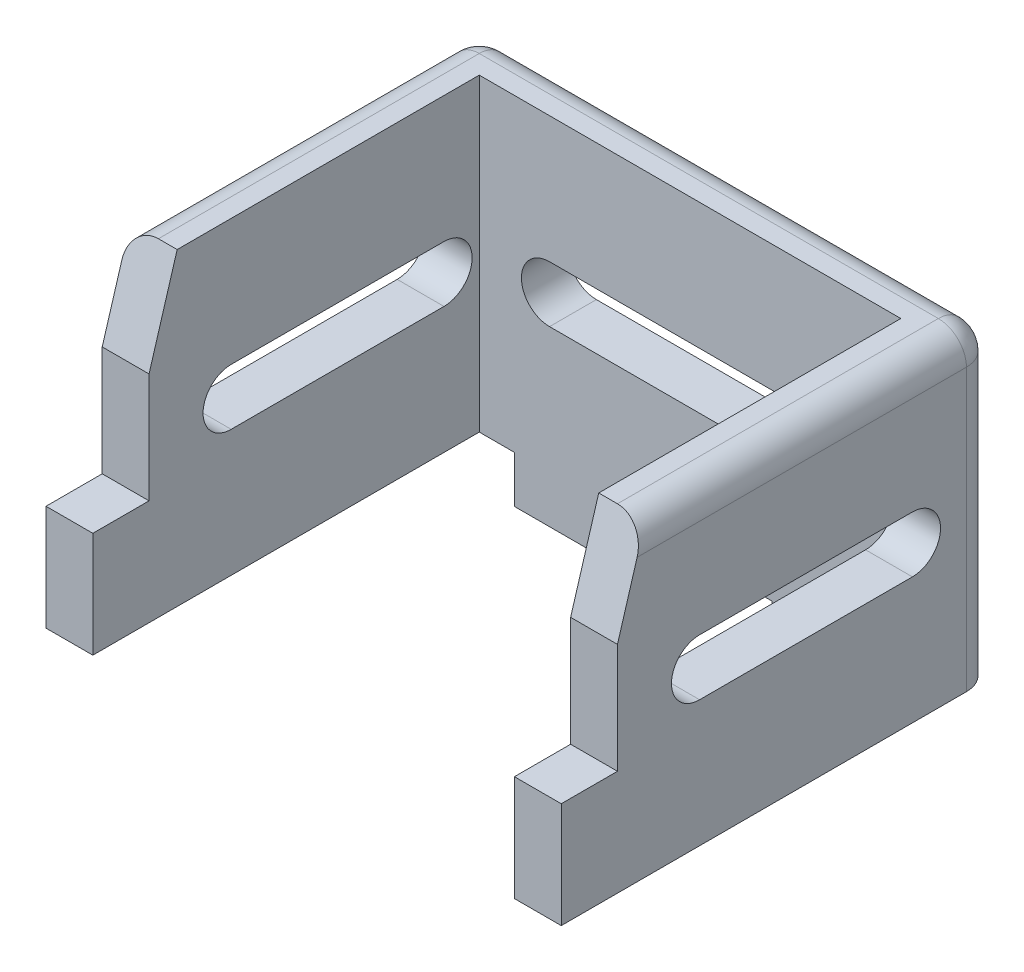
SolidWorks part; units mm, degrees
material "ABS"
ref_plane "Front Plane" through (0, 0, 0) normal (0, 0, 1) x (1, 0, 0)
ref_plane "Top Plane" through (0, 0, 0) normal (0, 1, 0) x (1, 0, 0)
ref_plane "Right Plane" through (0, 0, 0) normal (1, 0, 0) x (0, 0, -1)
sketch "Sketch1" plane through (0, 0, 0) normal (0, 1, 0) x (1, 0, 0)
  line L0 (-18.75, -2.5) -> (-17.25, 2.5)
  line L5 (-18.75, -2.5) -> (-8.75, -2.5) construction
  line L6 (-18.75, -2.5) -> (-18.75, 2.5) construction
  line L7 (-18.75, 2.5) -> (-8.75, 2.5) construction
  line L8 (-8.75, -2.5) -> (-8.75, 2.5) construction
  line L9 (-18.75, -2.5) -> (-8.75, 2.5) construction
  line L10 (-18.75, 2.5) -> (-8.75, -2.5) construction
  line L11 (-18.75, -2.5) -> (-8.75, -2.5)
  line L14 (-17.25, 2.5) -> (-10.25, 2.5)
  line L15 (-10.25, 2.5) -> (-8.75, -2.5)
  line L16 (0, 0) -> (-27.5, 0) construction
  line L17 (-27.5, -2.5) -> (27.5, -2.5) construction
  line L18 (-27.5, -2.5) -> (-27.5, 2.5) construction
  line L19 (-27.5, 2.5) -> (27.5, 2.5) construction
  line L20 (27.5, -2.5) -> (27.5, 2.5) construction
  line L21 (-27.5, -2.5) -> (27.5, 2.5) construction
  line L22 (-27.5, 2.5) -> (27.5, -2.5) construction
  line L23 (0, -2.5) -> (0, 2.5) construction
  line L25 (17.25, 2.5) -> (10.25, 2.5)
  line L26 (18.75, -2.5) -> (17.25, 2.5)
  line L27 (18.75, -2.5) -> (8.75, -2.5)
  line L28 (10.25, 2.5) -> (8.75, -2.5)
  point P0 (0, 0)
  point P5 (-13.75, 0)
  point P8 (0, 0)
  point P9 (-13.75, 0)
  point P17 (0, 0)
  point P23 (0, 0)
  point P27 (0, 0)
  dimension "D1" = 7
  dimension "D2" = 10
  dimension "D3" = 5
  dimension "D4" = 5
  dimension "D5" = 55
extrude "Boss-Extrude1" add sketch "Sketch1" against normal blind 5
sketch "Sketch2" plane through (0, 0, 0) normal (0, 1, 0) x (1, 0, 0)
  line L0 (0, -2.75) -> (0, 2.75) construction
  line L1 (27.5, 2.5) -> (-27.5, 2.5)
  line L2 (27.5, 2.5) -> (27.5, -2.5)
  line L3 (22.5, -2.5) -> (-22.5, -2.5)
  line L4 (-27.5, 2.5) -> (-27.5, -2.5)
  line L6 (-27.5, -2.5) -> (-27.5, -37.75)
  line L7 (-27.5, -37.75) -> (-22.5, -37.75)
  line L8 (-22.5, -2.5) -> (-22.5, -37.75)
  line L9 (27.5, -37.75) -> (22.5, -37.75)
  line L10 (22.5, -2.5) -> (22.5, -37.75)
  line L12 (27.5, -2.5) -> (27.5, -37.75)
  line L13 (-27.5, -2.5) -> (27.5, -2.5) construction
  dimension "D1" = 40.25
  dimension "D2" = 5
extrude "Boss-Extrude2" add sketch "Sketch2" along normal blind 33
sketch "Sketch3" plane through (-27.5, 0, 0) normal (-1, 0, 0) x (0, 0, 1)
  line L0 (37.75, 16.5) -> (-2.5, 16.5) construction
  line L1 (37.75, 33) -> (37.75, 0) construction
  line L2 (-2.5, 33) -> (-2.5, 0) construction
  line L3 (6.266, 16.5) -> (28.984, 16.5) construction
  line L4 (6.266, 19.5) -> (28.984, 19.5)
  line L5 (6.266, 13.5) -> (28.984, 13.5)
  arc A0 (6.266, 19.5) -> (6.266, 13.5) centre (6.266, 16.5) ccw
  arc A1 (28.984, 13.5) -> (28.984, 19.5) centre (28.984, 16.5) ccw
  point P8 (17.625, 16.5)
  dimension "D1" = 3
extrude "Cut-Extrude1" cut sketch "Sketch3" against normal through all both and the other way through all
sketch "Sketch4" plane through (0, 0, 37.75) normal (0, 0, 1) x (1, 0, 0)
  line L0 (-27.5, 0) -> (27.5, 0) construction
  line L1 (27.5, 0) -> (22.5, 0)
  line L2 (27.5, 0) -> (27.5, 11.27)
  line L3 (27.5, 11.27) -> (22.5, 11.27)
  line L4 (22.5, 0) -> (22.5, 11.27)
  line L5 (22.5, 33) -> (22.5, 0) construction
  line L6 (0, 0) -> (0, 33) construction
  line L7 (-22.5, 33) -> (22.5, 33) construction
  line L8 (27.5, 33) -> (27.5, 0) construction
  line L9 (-27.5, 11.27) -> (-22.5, 11.27)
  line L10 (-22.5, 0) -> (-22.5, 11.27)
  line L11 (-27.5, 0) -> (-22.5, 0)
  line L12 (-27.5, 0) -> (-27.5, 11.27)
  dimension "D1" = 11.27
extrude "Boss-Extrude3" add sketch "Sketch4" along normal blind 6
sketch "Sketch5" plane through (0, 0, 37.75) normal (0, 0, 1) x (1, 0, 0)
  line L0 (22.5, 33) -> (22.5, 0) construction
  line L1 (27.5, 33) -> (22.5, 33)
  line L2 (27.5, 33) -> (27.5, 24.27)
  line L3 (27.5, 24.27) -> (22.5, 24.27)
  line L4 (22.5, 33) -> (22.5, 24.27)
  line L5 (27.5, 11.27) -> (22.5, 11.27) construction
  line L6 (0, 33) -> (0, 0) construction
  dimension "D1" = 13
chamfer "Chamfer1" distance 10 distance2 3 2 edges at (-25, 33, 37.75) (25, 33, 37.75)
sketch "Sketch7" plane through (0, 0, 2.5) normal (0, 0, 1) x (1, 0, 0)
  line L0 (-15, 16.5) -> (15, 16.5) construction
  line L1 (0, 0) -> (0, 33) construction
  line L2 (-15, 19.5) -> (15, 19.5)
  line L3 (-15, 13.5) -> (15, 13.5)
  arc A0 (-15, 19.5) -> (-15, 13.5) centre (-15, 16.5) ccw
  arc A1 (15, 13.5) -> (15, 19.5) centre (15, 16.5) ccw
  point P4 (0, 16.5)
  dimension "D1" = 3
  dimension "D2" = 30
extrude "Cut-Extrude2" cut sketch "Sketch7" against normal through all
fillet "Fillet1" radius 3 2 edges at (-27.5, 16.5, -2.5) (27.5, 16.5, -2.5)
fillet "Fillet2" radius 3 5 edges at (-27.5, 33, 17.625) (-26.6213, 33, -1.6213) (0, 33, -2.5) (26.6213, 33, -1.6213) (27.5, 33, 17.625)
